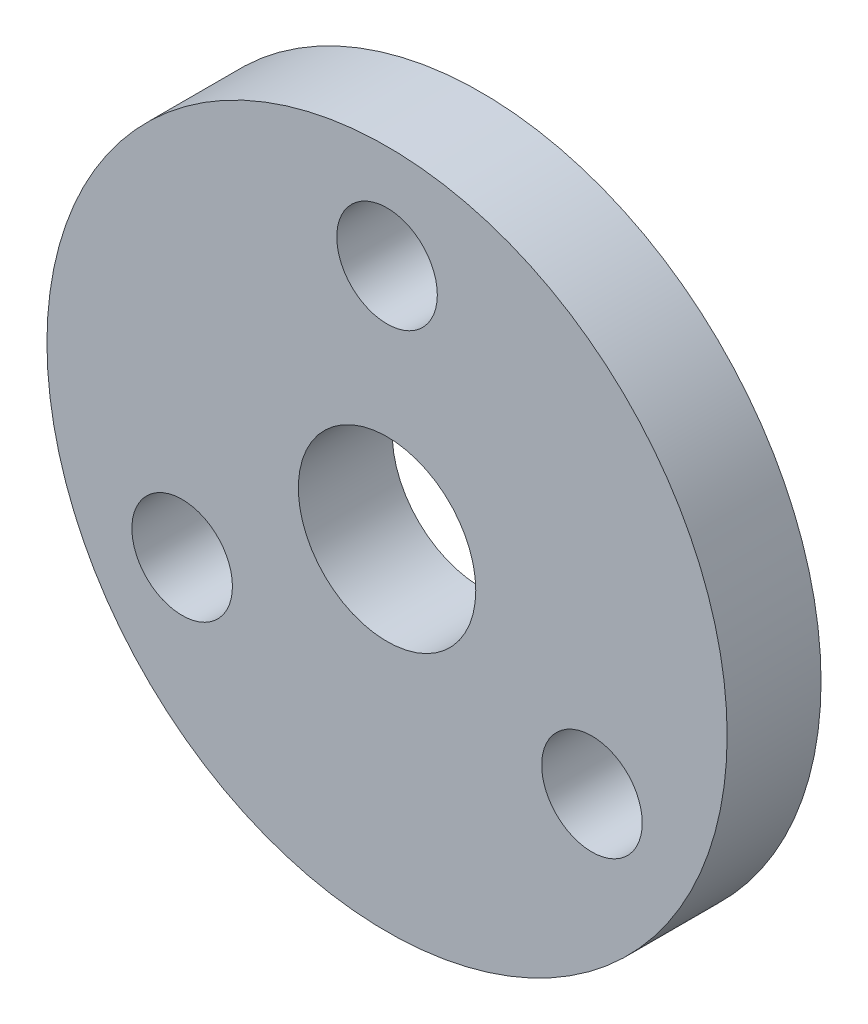
SolidWorks part; units mm, degrees
material "6061-T6 (SS)"
ref_plane "Front Plane" through (0, 0, 0) normal (0, 0, 1) x (1, 0, 0)
ref_plane "Top Plane" through (0, 0, 0) normal (0, 1, 0) x (1, 0, 0)
ref_plane "Right Plane" through (0, 0, 0) normal (1, 0, 0) x (0, 0, -1)
sketch "Sketch1" plane through (0, 0, 0) normal (0, 0, 1) x (1, 0, 0)
  circle A10 centre (10.1036, -10.1101) radius 3
  circle A11 centre (10.1036, -10.1101) radius 11.5 construction
  circle A12 centre (10.1036, -10.1101) radius 11.5
  circle A15 centre (3.1754, -14.1101) radius 1.7
  circle A16 centre (17.0318, -14.1101) radius 1.7
  circle A17 centre (10.1036, -2.1101) radius 1.7
  circle A20 centre (10.1036, -2.1101) radius 1.7 construction
  circle A21 centre (17.0318, -14.1101) radius 1.7 construction
  circle A22 centre (3.1754, -14.1101) radius 1.7 construction
  dimension "D1" = 6
extrude "Boss-Extrude1" add sketch "Sketch1" along normal blind 3.175
